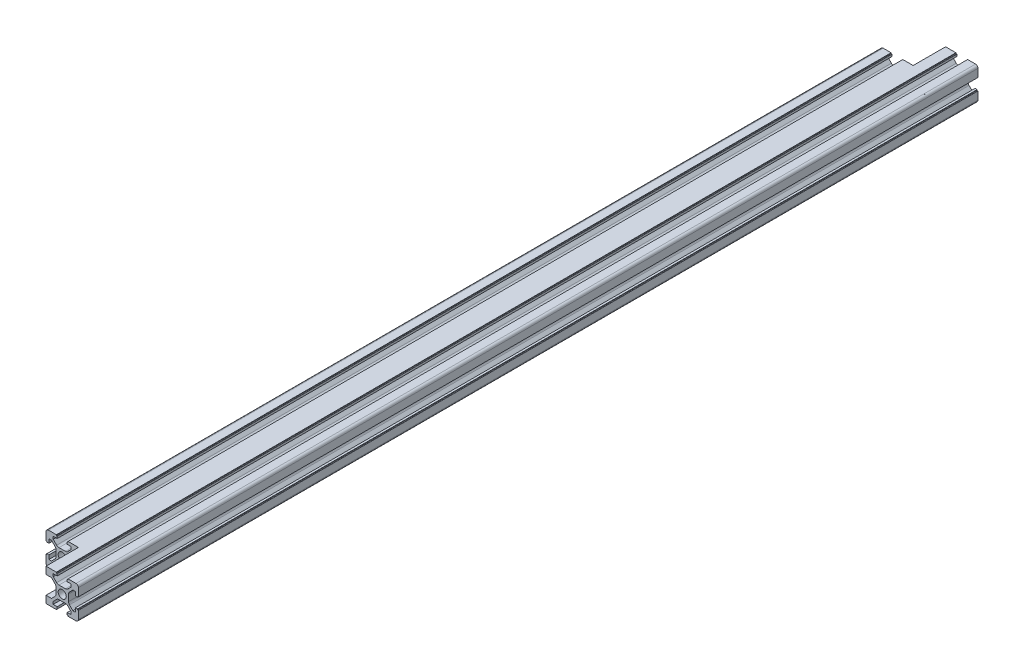
SolidWorks part; units mm, degrees
ref_plane "Спереди" through (0, 0, 0) normal (0, 0, 1) x (1, 0, 0)
ref_plane "Сверху" through (0, 0, 0) normal (0, 1, 0) x (1, 0, 0)
ref_plane "Справа" through (0, 0, 0) normal (1, 0, 0) x (0, 0, -1)
sketch "Sketch1" plane through (0, 0, 0) normal (0, 0, 1) x (1, 0, 0)
  line L0 (0, 10) -> (0, -10) construction
  line L1 (-10, -10) -> (10, -10) construction
  line L2 (-10, -10) -> (-10, 10) construction
  line L3 (-10, 10) -> (10, 10) construction
  line L4 (10, -10) -> (10, 10) construction
  line L5 (-10, -10) -> (10, 10) construction
  line L6 (-10, 10) -> (10, -10) construction
  line L7 (-30, 0) -> (10, 0) construction
  line L8 (0, 3.9) -> (-2.0109, 3.9)
  line L9 (-3.4251, 4.4858) -> (-5.5393, 6.6)
  line L10 (-5.5393, 6.6) -> (-5.5393, 8.2)
  line L11 (-5.5393, 8.2) -> (-3.1, 8.2)
  line L12 (-3.1, 8.2) -> (-3.1, 9.5)
  line L13 (-3.1, 9.5) -> (-3.4, 9.5)
  line L14 (-3.6, 9.7) -> (-3.6, 10)
  line L15 (-3.6, 10) -> (-8.5, 10)
  line L16 (-11.5, 10) -> (-8.5, 10)
  line L17 (-9.7, 3.6) -> (-10, 3.6)
  line L18 (-9.5, 3.1) -> (-9.5, 3.4)
  line L19 (-8.2, 3.1) -> (-9.5, 3.1)
  line L20 (-8.2, 5.5393) -> (-8.2, 3.1)
  line L21 (-6.6, 5.5393) -> (-8.2, 5.5393)
  line L22 (-4.4858, 3.4251) -> (-6.6, 5.5393)
  line L23 (-3.9, 0) -> (-3.9, 2.0109)
  line L24 (3.9, 0) -> (3.9, 2.0109)
  line L25 (4.4858, 3.4251) -> (6.6, 5.5393)
  line L26 (6.6, 5.5393) -> (8.2, 5.5393)
  line L27 (8.2, 5.5393) -> (8.2, 3.1)
  line L28 (8.2, 3.1) -> (9.5, 3.1)
  line L29 (9.5, 3.1) -> (9.5, 3.4)
  line L30 (9.7, 3.6) -> (10, 3.6)
  line L31 (10, 3.6) -> (10, 8.5)
  line L32 (3.6, 10) -> (8.5, 10)
  line L33 (3.6, 9.7) -> (3.6, 10)
  line L34 (3.1, 9.5) -> (3.4, 9.5)
  line L35 (3.1, 8.2) -> (3.1, 9.5)
  line L36 (5.5393, 8.2) -> (3.1, 8.2)
  line L37 (5.5393, 6.6) -> (5.5393, 8.2)
  line L38 (3.4251, 4.4858) -> (5.5393, 6.6)
  line L39 (0, 3.9) -> (2.0109, 3.9)
  line L40 (0, -3.9) -> (2.0109, -3.9)
  line L41 (3.4251, -4.4858) -> (5.5393, -6.6)
  line L42 (5.5393, -6.6) -> (5.5393, -8.2)
  line L43 (5.5393, -8.2) -> (3.1, -8.2)
  line L44 (3.1, -8.2) -> (3.1, -9.5)
  line L45 (3.1, -9.5) -> (3.4, -9.5)
  line L46 (3.6, -9.7) -> (3.6, -10)
  line L47 (3.6, -10) -> (8.5, -10)
  line L48 (10, -3.6) -> (10, -8.5)
  line L49 (9.7, -3.6) -> (10, -3.6)
  line L50 (9.5, -3.1) -> (9.5, -3.4)
  line L51 (8.2, -3.1) -> (9.5, -3.1)
  line L52 (8.2, -5.5393) -> (8.2, -3.1)
  line L53 (6.6, -5.5393) -> (8.2, -5.5393)
  line L54 (4.4858, -3.4251) -> (6.6, -5.5393)
  line L55 (3.9, 0) -> (3.9, -2.0109)
  line L56 (-3.9, 0) -> (-3.9, -2.0109)
  line L57 (-4.4858, -3.4251) -> (-6.6, -5.5393)
  line L58 (-6.6, -5.5393) -> (-8.2, -5.5393)
  line L59 (-8.2, -5.5393) -> (-8.2, -3.1)
  line L60 (-8.2, -3.1) -> (-9.5, -3.1)
  line L61 (-9.5, -3.1) -> (-9.5, -3.4)
  line L62 (-9.7, -3.6) -> (-10, -3.6)
  line L63 (-11.5, -10) -> (-8.5, -10)
  line L64 (-3.6, -10) -> (-8.5, -10)
  line L65 (-3.6, -9.7) -> (-3.6, -10)
  line L66 (-3.1, -9.5) -> (-3.4, -9.5)
  line L67 (-3.1, -8.2) -> (-3.1, -9.5)
  line L68 (-5.5393, -8.2) -> (-3.1, -8.2)
  line L69 (-5.5393, -6.6) -> (-5.5393, -8.2)
  line L70 (-3.4251, -4.4858) -> (-5.5393, -6.6)
  line L71 (0, -3.9) -> (-2.0109, -3.9)
  line L72 (-10, 10) -> (-30, -10) construction
  line L73 (-10, -10) -> (-30, 10) construction
  line L74 (-30, -10) -> (-30, 10) construction
  line L75 (-10, 10) -> (-30, 10) construction
  line L76 (-10, -10) -> (-30, -10) construction
  line L77 (-20, 10) -> (-20, -10) construction
  line L78 (-20, -3.9) -> (-17.9891, -3.9)
  line L79 (-16.5749, -4.4858) -> (-14.4607, -6.6)
  line L80 (-14.4607, -6.6) -> (-14.4607, -8.2)
  line L81 (-14.4607, -8.2) -> (-16.9, -8.2)
  line L82 (-16.9, -8.2) -> (-16.9, -9.5)
  line L83 (-16.9, -9.5) -> (-16.6, -9.5)
  line L84 (-16.4, -9.7) -> (-16.4, -10)
  line L85 (-16.4, -10) -> (-11.5, -10)
  line L86 (-10.2, -3.1) -> (-10.2, -3.4)
  line L87 (-11.5, -3.1) -> (-10.2, -3.1)
  line L88 (-11.5, -5.5393) -> (-11.5, -3.1)
  line L89 (-13.1, -5.5393) -> (-11.5, -5.5393)
  line L90 (-15.2142, -3.4251) -> (-13.1, -5.5393)
  line L91 (-15.8, 0) -> (-15.8, -2.0109)
  line L92 (-23.9, 0) -> (-23.9, -2.0109)
  line L93 (-24.4858, -3.4251) -> (-26.6, -5.5393)
  line L94 (-26.6, -5.5393) -> (-28.2, -5.5393)
  line L95 (-28.2, -5.5393) -> (-28.2, -3.1)
  line L96 (-28.2, -3.1) -> (-29.5, -3.1)
  line L97 (-29.5, -3.1) -> (-29.5, -3.4)
  line L98 (-29.7, -3.6) -> (-30, -3.6)
  line L99 (-30, -3.6) -> (-30, -8.5)
  line L100 (-23.6, -10) -> (-28.5, -10)
  line L101 (-23.6, -9.7) -> (-23.6, -10)
  line L102 (-23.1, -9.5) -> (-23.4, -9.5)
  line L103 (-23.1, -8.2) -> (-23.1, -9.5)
  line L104 (-25.5393, -8.2) -> (-23.1, -8.2)
  line L105 (-25.5393, -6.6) -> (-25.5393, -8.2)
  line L106 (-23.4251, -4.4858) -> (-25.5393, -6.6)
  line L107 (-20, -3.9) -> (-22.0109, -3.9)
  line L108 (-20, 3.9) -> (-22.0109, 3.9)
  line L109 (-23.4251, 4.4858) -> (-25.5393, 6.6)
  line L110 (-25.5393, 6.6) -> (-25.5393, 8.2)
  line L111 (-25.5393, 8.2) -> (-23.1, 8.2)
  line L112 (-23.1, 8.2) -> (-23.1, 9.5)
  line L113 (-23.1, 9.5) -> (-23.4, 9.5)
  line L114 (-23.6, 9.7) -> (-23.6, 10)
  line L115 (-23.6, 10) -> (-28.5, 10)
  line L116 (-30, 3.6) -> (-30, 8.5)
  line L117 (-29.7, 3.6) -> (-30, 3.6)
  line L118 (-29.5, 3.1) -> (-29.5, 3.4)
  line L119 (-28.2, 3.1) -> (-29.5, 3.1)
  line L120 (-28.2, 5.5393) -> (-28.2, 3.1)
  line L121 (-26.6, 5.5393) -> (-28.2, 5.5393)
  line L122 (-24.4858, 3.4251) -> (-26.6, 5.5393)
  line L123 (-23.9, 0) -> (-23.9, 2.0109)
  line L124 (-15.8, 0) -> (-15.8, 2.0109)
  line L125 (-15.2142, 3.4251) -> (-13.1, 5.5393)
  line L126 (-13.1, 5.5393) -> (-11.5, 5.5393)
  line L127 (-11.5, 5.5393) -> (-11.5, 3.1)
  line L128 (-11.5, 3.1) -> (-10.2, 3.1)
  line L129 (-10.2, 3.1) -> (-10.2, 3.4)
  line L130 (-16.4, 10) -> (-11.5, 10)
  line L131 (-16.4, 9.7) -> (-16.4, 10)
  line L132 (-16.9, 9.5) -> (-16.6, 9.5)
  line L133 (-16.9, 8.2) -> (-16.9, 9.5)
  line L134 (-14.4607, 8.2) -> (-16.9, 8.2)
  line L135 (-14.4607, 6.6) -> (-14.4607, 8.2)
  line L136 (-16.5749, 4.4858) -> (-14.4607, 6.6)
  line L137 (-20, 3.9) -> (-17.9891, 3.9)
  line L138 (-10, -3.6) -> (-10, -8.5) [skipped]
  circle A0 centre (0, 0) radius 2.5
  arc A2 (-2.0109, 3.9) -> (-3.4251, 4.4858) centre (-2.0109, 5.9) cw
  arc A3 (-3.4, 9.5) -> (-3.6, 9.7) centre (-3.4, 9.7) cw
  arc A4 (-9.5, 3.4) -> (-9.7, 3.6) centre (-9.7, 3.4) ccw
  arc A5 (-3.9, 2.0109) -> (-4.4858, 3.4251) centre (-5.9, 2.0109) ccw
  arc A6 (10, 8.5) -> (8.5, 10) centre (8.5, 8.5) ccw
  arc A7 (3.9, 2.0109) -> (4.4858, 3.4251) centre (5.9, 2.0109) cw
  arc A8 (9.5, 3.4) -> (9.7, 3.6) centre (9.7, 3.4) cw
  arc A9 (3.4, 9.5) -> (3.6, 9.7) centre (3.4, 9.7) ccw
  arc A10 (2.0109, 3.9) -> (3.4251, 4.4858) centre (2.0109, 5.9) ccw
  arc A11 (8.5, -10) -> (10, -8.5) centre (8.5, -8.5) ccw
  arc A12 (2.0109, -3.9) -> (3.4251, -4.4858) centre (2.0109, -5.9) cw
  arc A13 (3.4, -9.5) -> (3.6, -9.7) centre (3.4, -9.7) cw
  arc A14 (9.5, -3.4) -> (9.7, -3.6) centre (9.7, -3.4) ccw
  arc A15 (3.9, -2.0109) -> (4.4858, -3.4251) centre (5.9, -2.0109) ccw
  arc A17 (-3.9, -2.0109) -> (-4.4858, -3.4251) centre (-5.9, -2.0109) cw
  arc A18 (-9.5, -3.4) -> (-9.7, -3.6) centre (-9.7, -3.4) cw
  arc A19 (-3.4, -9.5) -> (-3.6, -9.7) centre (-3.4, -9.7) ccw
  arc A20 (-2.0109, -3.9) -> (-3.4251, -4.4858) centre (-2.0109, -5.9) ccw
  arc A21 (-17.9891, -3.9) -> (-16.5749, -4.4858) centre (-17.9891, -5.9) cw
  arc A22 (-16.6, -9.5) -> (-16.4, -9.7) centre (-16.6, -9.7) cw
  arc A23 (-10.2, -3.4) -> (-10, -3.6) centre (-10, -3.4) ccw
  arc A24 (-15.8, -2.0109) -> (-15.2142, -3.4251) centre (-13.8, -2.0109) ccw
  arc A26 (-23.9, -2.0109) -> (-24.4858, -3.4251) centre (-25.9, -2.0109) cw
  arc A27 (-29.5, -3.4) -> (-29.7, -3.6) centre (-29.7, -3.4) cw
  arc A28 (-23.4, -9.5) -> (-23.6, -9.7) centre (-23.4, -9.7) ccw
  arc A29 (-22.0109, -3.9) -> (-23.4251, -4.4858) centre (-22.0109, -5.9) ccw
  arc A30 (-28.5, -10) -> (-30, -8.5) centre (-28.5, -8.5) cw
  arc A31 (-22.0109, 3.9) -> (-23.4251, 4.4858) centre (-22.0109, 5.9) cw
  arc A32 (-23.4, 9.5) -> (-23.6, 9.7) centre (-23.4, 9.7) cw
  arc A33 (-29.5, 3.4) -> (-29.7, 3.6) centre (-29.7, 3.4) ccw
  arc A34 (-23.9, 2.0109) -> (-24.4858, 3.4251) centre (-25.9, 2.0109) ccw
  arc A35 (-30, 8.5) -> (-28.5, 10) centre (-28.5, 8.5) cw
  arc A36 (-15.8, 2.0109) -> (-15.2142, 3.4251) centre (-13.8, 2.0109) cw
  arc A37 (-10.2, 3.4) -> (-10, 3.6) centre (-10, 3.4) cw
  arc A38 (-16.6, 9.5) -> (-16.4, 9.7) centre (-16.6, 9.7) ccw
  arc A39 (-17.9891, 3.9) -> (-16.5749, 4.4858) centre (-17.9891, 5.9) ccw
  circle A41 centre (-20, 0) radius 2.5
  point P0 (0, 0)
  point P40 (-10, 0)
  point P42 (0, 0)
  point P70 (0, 0)
  point P98 (0, 0)
  point P126 (0, 0)
  point P227 (-20, 0)
  point P228 (-20, 0)
  point P229 (-20, 0)
  point P230 (-20, 0)
  point P231 (-20, 0)
  dimension "D3" = 5
  dimension "D12" = 2
  dimension "D13" = 0.2
  dimension "D1" = 20
  dimension "D2" = 20
  dimension "D5" = 6.2
  dimension "D6" = 7.2
  dimension "D7" = 1.8
  dimension "D8" = 0.5
  dimension "D9" = 3.4
  dimension "D10" = 1.5
  dimension "D11" = 6.1
  dimension "D14" = 4
extrude "Extrude1" add sketch "Sketch1" along normal mid plane 555
sketch "Sketch2" plane through (0, 0, 277.5) normal (0, 0, 1) x (1, 0, 0)
  line L1 (-11.5, 5.5393) -> (-8.2, 5.5393)
  line L2 (-11.5, 5.5393) -> (-11.5, -5.5393)
  line L3 (-11.5, -5.5393) -> (-8.2, -5.5393)
  line L4 (-8.2, 5.5393) -> (-8.2, -5.5393)
extrude "Cut-Extrude1" cut sketch "Sketch2" against normal through all both and the other way through all
sketch "Sketch3" plane through (0, 0, 277.5) normal (0, 0, 1) x (1, 0, 0)
  line L0 (-16.4, -10) -> (-3.6, -10) construction
  line L1 (-10, -10) -> (-31.9635, -10)
  line L2 (-10, -10) -> (-10, 11.4441)
  line L3 (-10, 11.4441) -> (-31.9635, 11.4441)
  line L4 (-31.9635, -10) -> (-31.9635, 11.4441)
extrude "Cut-Extrude2" cut sketch "Sketch3" against normal blind 20
mirror "Mirror1" about plane through (0, 0, 0) normal (0, 0, 1) of "Cut-Extrude2"
